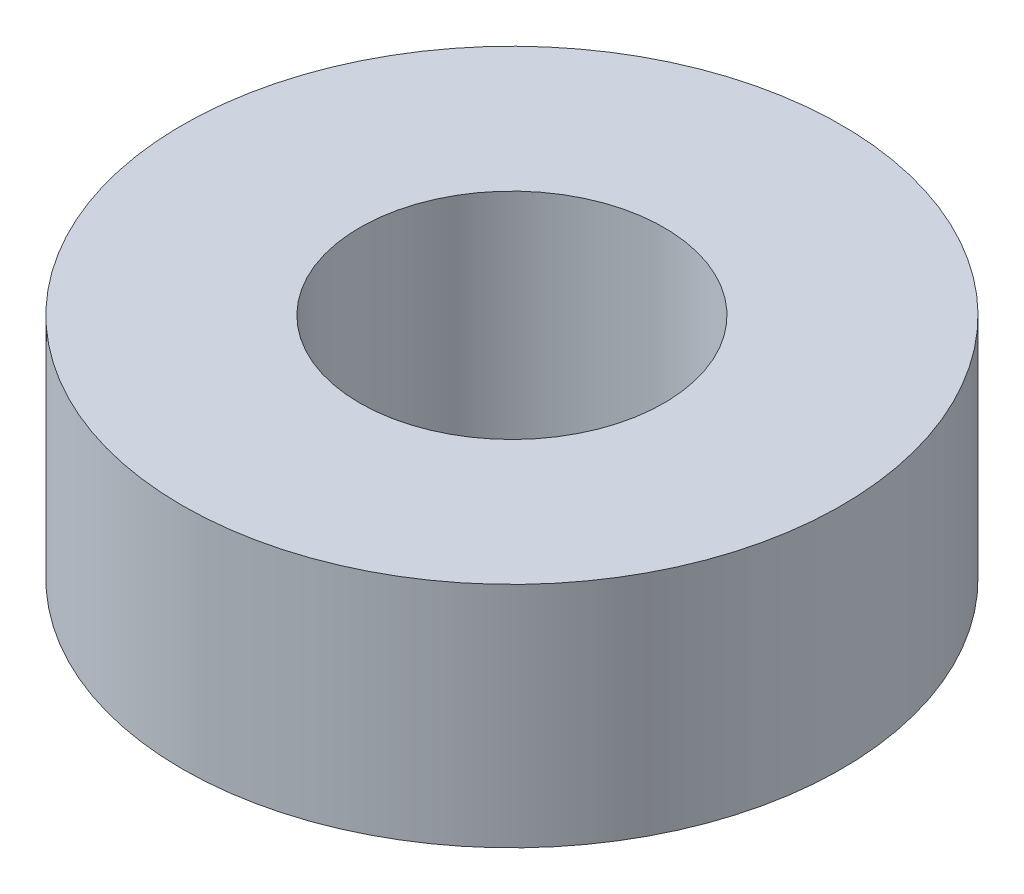
SolidWorks part; units mm, degrees
ref_plane "Front Plane" through (0, 0, 0) normal (0, 0, 1) x (1, 0, 0)
ref_plane "Top Plane" through (0, 0, 0) normal (0, 1, 0) x (1, 0, 0)
ref_plane "Right Plane" through (0, 0, 0) normal (1, 0, 0) x (0, 0, -1)
sketch "Sketch1" plane through (0, 0, 0) normal (0, 1, 0) x (1, 0, 0)
  circle A0 centre (0, 0) radius 13
  circle A1 centre (0, 0) radius 6
  dimension "D1" = 12
  dimension "D2" = 26
extrude "Boss-Extrude1" add sketch "Sketch1" along normal blind 9
